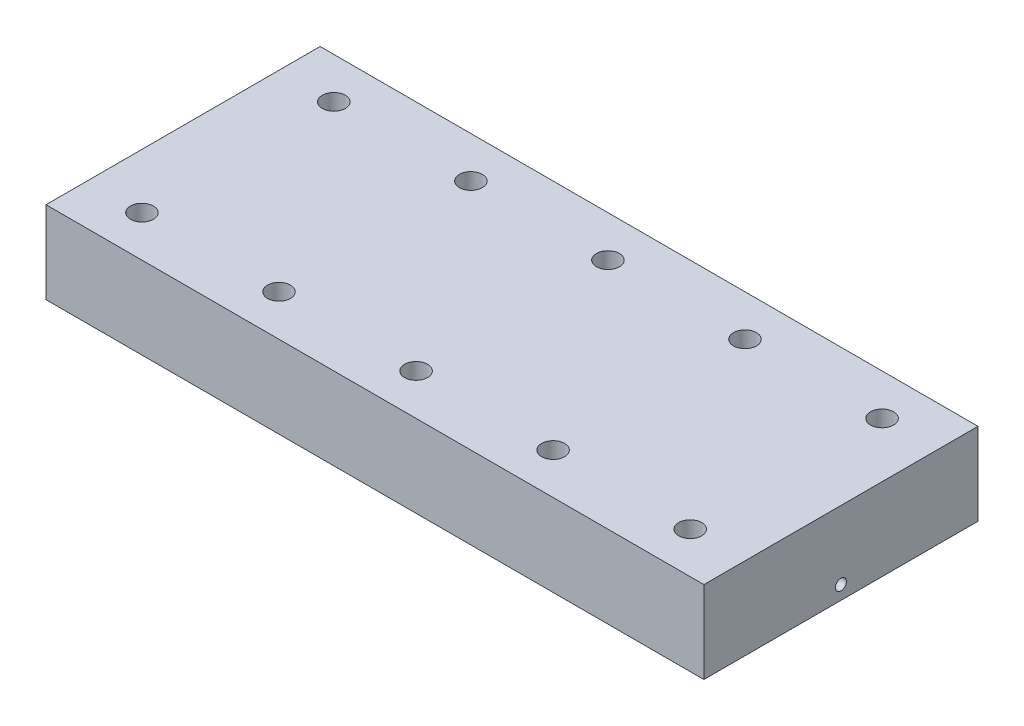
SolidWorks part; units mm, degrees
ref_plane "Front Plane" through (0, 0, 0) normal (0, 0, 1) x (1, 0, 0)
ref_plane "Top Plane" through (0, 0, 0) normal (0, 1, 0) x (1, 0, 0)
ref_plane "Right Plane" through (0, 0, 0) normal (1, 0, 0) x (0, 0, -1)
sketch "Sketch2" plane through (0, 0, 0) normal (0, 1, 0) x (1, 0, 0)
  line L0 (-46.8981, 34.5466) -> (-46.8981, -15.4534)
  line L1 (-46.8981, -15.4534) -> (73.1019, -15.4534)
  line L2 (73.1019, -15.4534) -> (73.1019, 34.5466)
  line L3 (73.1019, 34.5466) -> (-46.8981, 34.5466)
  dimension "D1" = 120
  dimension "D2" = 50
extrude "Boss-Extrude1" add sketch "Sketch2" along normal blind 15
sketch "Sketch3" plane through (0, 0, 0) normal (0, 1, 0) x (1, 0, 0)
  line L0 (74.3548, 9.5466) -> (-56.2815, 9.5466) construction
  line L1 (63.1019, 9.5466) -> (63.1019, 17.0466)
  line L2 (63.1019, 17.0466) -> (3.1019, 17.0466)
  line L3 (3.1019, 17.0466) -> (3.1019, 19.5466)
  line L4 (3.1019, 19.5466) -> (-36.8981, 19.5466)
  line L5 (-36.8981, 19.5466) -> (-36.8981, 9.5466)
  line L6 (-36.8981, 9.5466) -> (63.1019, 9.5466)
  line L7 (73.1019, -15.4534) -> (73.1019, 34.5466) construction
  line L9 (-46.8981, -15.4534) -> (73.1019, -15.4534) construction
  dimension "D1" = 60
  dimension "D2" = 40
  dimension "D3" = 10
  dimension "D4" = 25
  dimension "D5" = 10
  dimension "D6" = 7.5
sketch "Skizze7" plane through (-46.8981, 0, 0) normal (-1, 0, 0) x (0, 0, 1)
  line L1 (-34.5466, 0) -> (15.4534, 0) construction
  line L3 (-9.5466, -6.0172) -> (-9.5466, 6.0172) construction
  line L4 (15.4534, 15) -> (15.4534, 0) construction
  line L5 (-34.5466, 15) -> (-34.5466, 0) construction
  circle A0 centre (-9.5466, 2.5) radius 1.5
  dimension "D1" = 3
  dimension "D2" = 2.5
extrude "Schnitt-Linear austragen6" cut sketch "Skizze7" against normal blind 10
revolve "Schnitt-Rotation1" cut sketch "Sketch3" angle 360 about L0
sketch "Skizze10" plane through (0, 0, 0) normal (0, -1, 0) x (1, 0, 0)
  line L0 (63.1019, -17.0466) -> (3.1019, -17.0466) construction
  line L1 (53.1019, -17.0466) -> (40.6019, -17.0466)
  line L2 (53.1019, -17.0466) -> (53.1019, -14.5466)
  line L3 (53.1019, -14.5466) -> (40.6019, -14.5466)
  line L4 (40.6019, -17.0466) -> (40.6019, -14.5466)
  line L5 (63.1019, -2.0466) -> (63.1019, -17.0466) construction
  line L10 (85.7448, -9.5466) -> (-66.8579, -9.5466) construction
  line L11 (-46.8981, 15.4534) -> (73.1019, 15.4534) construction
  line L12 (73.1019, -34.5466) -> (-46.8981, -34.5466) construction
  dimension "D1" = 10
  dimension "D2" = 12.5
  dimension "D5" = 2.5
revolve "Rotation3" add sketch "Skizze10" angle 180 about L10
sketch "Skizze11" plane through (0, 0, 0) normal (0, -1, 0) x (1, 0, 0)
  line L0 (40.6019, -17.0466) -> (3.1019, -17.0466) construction
  line L1 (28.1019, -17.0466) -> (15.6019, -17.0466)
  line L2 (28.1019, -17.0466) -> (28.1019, -14.5466)
  line L3 (28.1019, -14.5466) -> (15.6019, -14.5466)
  line L4 (15.6019, -17.0466) -> (15.6019, -14.5466)
  line L5 (53.1019, -14.5466) -> (40.6019, -14.5466) construction
  line L6 (40.6019, -14.5466) -> (40.6019, -17.0466) construction
  line L7 (95.0378, -9.5466) -> (-94.5432, -9.5466) construction
  line L8 (-46.8981, 15.4534) -> (73.1019, 15.4534) construction
  line L9 (73.1019, -34.5466) -> (-46.8981, -34.5466) construction
  point P10 (40.6019, -15.7966)
  dimension "D1" = 12.5
  dimension "D2" = 12.5
revolve "Rotation4" add sketch "Skizze11" angle 180 about L7
sketch "Skizze12" plane through (0, 0, 0) normal (0, -1, 0) x (1, 0, 0)
  line L0 (73.1019, 15.4534) -> (73.1019, -34.5466) construction
  line L1 (-46.8981, -34.5466) -> (-46.8981, 15.4534) construction
  line L2 (-46.8981, 15.4534) -> (73.1019, 15.4534) construction
  line L3 (-46.8981, 15.4534) -> (73.1019, 15.4534) construction
  circle A0 centre (-36.8981, 7.9534) radius 2.1
  circle A1 centre (13.1019, 7.9534) radius 2.1
  circle A2 centre (63.1019, 7.9534) radius 2.1
  circle A3 centre (38.1019, 7.9534) radius 2.1
  circle A4 centre (-11.8981, 7.9534) radius 2.1
  dimension "D3" = 4.2
  dimension "D6" = 4.2
  dimension "D7" = 4.2
  dimension "D8" = 25
  dimension "D9" = 25
  dimension "D10" = 50
  dimension "D11" = 7.5
  dimension "D2" = 10
  dimension "D4" = 10
  dimension "D5" = 7.5
  dimension "D1" = 3
ref_plane "Ebene6" through (0, 0, -9.5466) normal (0, 0, 1) x (1, 0, 0)
extrude "Schnitt-Linear austragen7" cut sketch "Skizze12" against normal through all
mirror "Spiegeln1" about plane through (0, 0, -9.5466) normal (0, 0, 1) of "Schnitt-Linear austragen7"
sketch "Skizze13" plane through (-46.8981, 0, 0) normal (-1, 0, 0) x (0, 0, 1)
  line L0 (-34.5466, 0) -> (15.4534, 0) construction
  line L1 (15.4534, 15) -> (0.4534, 15)
  line L2 (15.4534, 15) -> (15.4534, 5)
  line L3 (15.4534, 5) -> (0.4534, 5)
  line L4 (0.4534, 15) -> (0.4534, 5)
  line L5 (-34.5466, 0) -> (15.4534, 0) construction
  line L6 (-34.5466, 15) -> (-19.5466, 15)
  line L7 (-34.5466, 15) -> (-34.5466, 5)
  line L8 (-34.5466, 5) -> (-19.5466, 5)
  line L9 (-19.5466, 15) -> (-19.5466, 5)
  dimension "D1" = 15
  dimension "D2" = 5
  dimension "D3" = 15
  dimension "D4" = 5
fillet "Fillet2" radius 1 1 edges at (3.1019, 7.5, -9.5466)
fillet "Fillet3" radius 1 1 edges at (15.6019, 5, -9.5466)
fillet "Fillet4" radius 1 1 edges at (28.1019, 5, -9.5466)
fillet "Fillet5" radius 1 1 edges at (40.6019, 5, -9.5466)
fillet "Fillet6" radius 1 1 edges at (53.1019, 5, -9.5466)
fillet "Fillet7" radius 1 1 edges at (3.1019, 10, -9.5466)
ref_plane "Plane1" through (83.1019, 0, 0) normal (1, 0, 0) x (0, 0, -1)
sketch "Sketch4" plane through (83.1019, 0, 0) normal (1, 0, 0) x (0, 0, -1)
  circle A0 centre (9.5466, 2.5) radius 1
  dimension "D1" = 2
extrude "Cut-Extrude1" cut sketch "Sketch4" against normal blind 25
fillet "Fillet8" radius 1 1 edges at (15.6019, 7.5, -9.5466)
fillet "Fillet9" radius 1 1 edges at (28.1019, 7.5, -9.5466)
fillet "Fillet10" radius 1 1 edges at (40.6019, 7.5, -9.5466)
fillet "Fillet11" radius 1 1 edges at (53.1019, 7.5, -9.5466)
